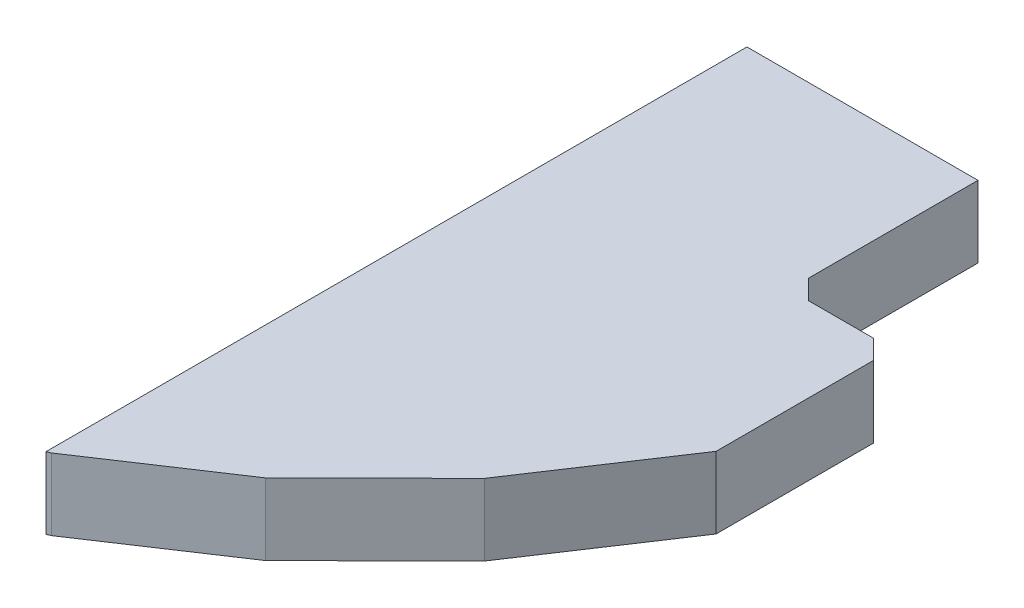
SolidWorks part; units mm, degrees
material "Copper"
ref_plane "Front Plane" through (0, 0, 0) normal (0, 0, 1) x (1, 0, 0)
ref_plane "Top Plane" through (0, 0, 0) normal (0, 1, 0) x (1, 0, 0)
ref_plane "Right Plane" through (0, 0, 0) normal (1, 0, 0) x (0, 0, -1)
sketch "Sketch1" plane through (0, 0, 0) normal (0, 1, 0) x (1, 0, 0)
  line B0 (0, 0) -> (23.9, 0)
  line B1 (0, 0) -> (0, -72.5161)
  line B2 (0, -72.5161) -> (0.3887, -72.3559)
  line B3 (23.9, 0) -> (23.9, -17.55)
  line B4 (23.9, -17.55) -> (25.9, -19.55)
  line B5 (25.9, -19.55) -> (32.63, -19.55)
  line B6 (32.63, -19.55) -> (34.63, -21.55)
  line B7 (34.63, -21.55) -> (34.63, -37.8228)
  line B8 (34.63, -37.8228) -> (25.0717, -52.2313)
  line B9 (25.0717, -52.2313) -> (13.7166, -63.5034)
  line B10 (13.7166, -63.5034) -> (0.3887, -72.3559)
sketch_block_instance "Base_Block_Half-1"
sketch_block "Base_Block_Half"
extrude "Boss-Extrude1" add sketch "Sketch1" along normal blind 7.4092
equation "\"D1@Boss-Extrude1\"=0.14370079+0.148"
